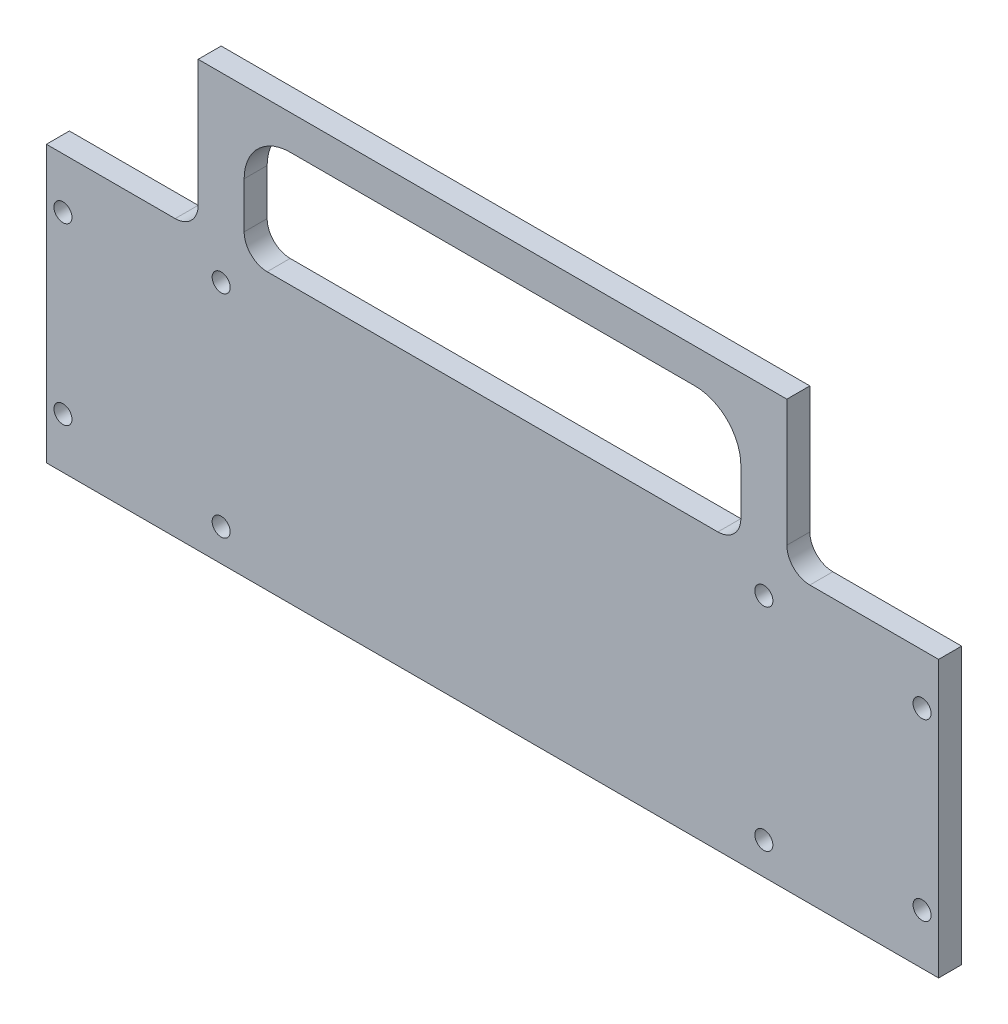
SolidWorks part; units mm, degrees
material "6061-T6 (SS)"
ref_plane "Front Plane" through (0, 0, 0) normal (0, 0, 1) x (1, 0, 0)
ref_plane "Top Plane" through (0, 0, 0) normal (0, 1, 0) x (1, 0, 0)
ref_plane "Right Plane" through (0, 0, 0) normal (1, 0, 0) x (0, 0, -1)
sketch "Sketch1" plane through (0, 0, 0) normal (0, 0, 1) x (1, 0, 0)
  line L1 (-123.19, 38.1) -> (123.19, 38.1)
  line L2 (-123.19, 38.1) -> (-123.19, -38.1)
  line L3 (-123.19, -38.1) -> (123.19, -38.1)
  line L4 (123.19, 38.1) -> (123.19, -38.1)
  line L5 (-123.19, 38.1) -> (123.19, -38.1) construction
  line L6 (-123.19, -38.1) -> (123.19, 38.1) construction
  point P0 (0, 0)
  dimension "D1" = 76.2
  dimension "D2" = 246.38
extrude "Boss-Extrude1" add sketch "Sketch1" along normal blind 6.35
sketch "Sketch2" plane through (0, 0, 6.35) normal (0, 0, 1) x (1, 0, 0)
  line L0 (123.19, -38.1) -> (123.19, 38.1) construction
  line L1 (-74.93, 29.21) -> (74.93, 29.21) construction
  line L2 (-74.93, 29.21) -> (-74.93, -29.21) construction
  line L3 (-74.93, -29.21) -> (74.93, -29.21) construction
  line L4 (74.93, 29.21) -> (74.93, -29.21) construction
  line L5 (-74.93, 29.21) -> (74.93, -29.21) construction
  line L6 (-74.93, -29.21) -> (74.93, 29.21) construction
  line L7 (118.618, -24.13) -> (-118.618, -24.13) construction
  line L8 (118.618, -24.13) -> (118.618, 24.13) construction
  line L9 (118.618, 24.13) -> (-118.618, 24.13) construction
  line L10 (-118.618, -24.13) -> (-118.618, 24.13) construction
  line L11 (118.618, -24.13) -> (-118.618, 24.13) construction
  line L12 (118.618, 24.13) -> (-118.618, -24.13) construction
  point P0 (0, 0)
  point P6 (0, 0)
  dimension "D1" = 149.86
  dimension "D2" = 58.42
  dimension "D3" = 4.572
  dimension "D4" = 48.26
hole_wizard "#10 Clearance Hole1" positions "Sketch3" profile "Sketch4" hole size "#10" standard "ANSI Inch" end condition through all
sketch "Sketch3" plane through (0, 0, 6.35) normal (0, 0, 1) x (1, 0, 0)
  point P0 (-74.93, 29.21)
  point P3 (-74.93, -29.21)
  point P6 (74.93, 29.21)
  point P9 (74.93, -29.21)
  point P12 (-118.618, 24.13)
  point P15 (-118.618, -24.13)
  point P18 (118.618, 24.13)
  point P21 (118.618, -24.13)
sketch "Sketch4" plane through (-74.93, 29.21, 6.35) normal (1, 0, 0) x (0, -1, 0)
  line L0 (0, 0) -> (0, 6.35)
  line L1 (0, 6.35) -> (2.4892, 6.35)
  line L2 (2.4892, 6.35) -> (2.4892, 0)
  line L5 (2.4892, 0) -> (0, 0)
  line L11 (0, -6.35) -> (0, 107.95) construction
  dimension "Thru Hole Dia." = 4.9784
  dimension "Thru Hole Depth" = 6.35
sketch "Sketch5" plane through (0, 0, 6.35) normal (0, 0, 1) x (1, 0, 0)
  line L0 (123.19, 38.1) -> (-123.19, 38.1) construction
  line L1 (-81.28, 38.1) -> (-68.58, 38.1)
  line L2 (-81.28, 38.1) -> (-81.28, 69.85)
  line L3 (-81.28, 69.85) -> (-68.58, 69.85)
  line L4 (-68.58, 38.1) -> (-68.58, 69.85)
  line L6 (-81.28, 69.85) -> (0, 69.85)
  line L7 (-81.28, 69.85) -> (-81.28, 79.375)
  line L8 (-81.28, 79.375) -> (0, 79.375)
  line L9 (0, 69.85) -> (0, 79.375)
  line L11 (-81.28, 47.2714) -> (-81.28, 79.375)
  point P9 (-74.93, 38.1)
  point P10 (-74.93, 29.21)
  line M15 (123.19, 38.1) -> (-123.19, 38.1)
  dimension "D1" = 12.7
  dimension "D2" = 9.525
  dimension "D3" = 41.275
extrude "Boss-Extrude2" add sketch "Sketch5" against normal up to surface (6.35 mm away) contours L4 L3 L2 M15 | L6 L9 L8 L7 L3 up to face at (-72.4408, 29.21, 0)
fillet "Fillet1" radius 12.7 1 edges at (-68.58, 69.85, 3.175)
mirror "Mirror1" about plane through (0, 0, 0) normal (1, 0, 0) of "Boss-Extrude2", "Fillet1"
fillet "Fillet2" radius 6.35 2 edges at (68.58, 38.1, 3.175) (-68.58, 38.1, 3.175)
fillet "Fillet3" radius 6.35 2 edges at (-81.28, 38.1, 3.175) (81.28, 38.1, 3.175)
